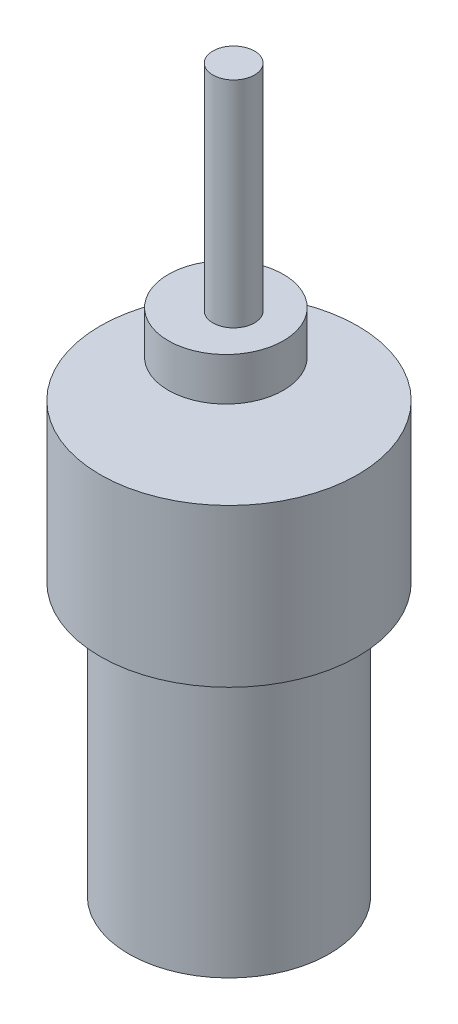
SolidWorks part; units mm, degrees
ref_plane "Front Plane" through (0, 0, 0) normal (0, 0, 1) x (1, 0, 0)
ref_plane "Top Plane" through (0, 0, 0) normal (0, 1, 0) x (1, 0, 0)
ref_plane "Right Plane" through (0, 0, 0) normal (1, 0, 0) x (0, 0, -1)
sketch "Sketch2" plane through (0, 0, 0) normal (0, 1, 0) x (1, 0, 0)
  circle A0 centre (0, 0) radius 14
  dimension "D1" = 28
extrude "Boss-Extrude1" add sketch "Sketch2" along normal blind 38
sketch "Sketch3" plane through (0, 38, 0) normal (0, 1, 0) x (1, 0, 0)
  circle A0 centre (0, 0) radius 18
  dimension "D1" = 36
extrude "Boss-Extrude2" add sketch "Sketch3" along normal blind 22
sketch "Sketch4" plane through (0, 60, 0) normal (0, 1, 0) x (1, 0, 0)
  circle A0 centre (-5.4402, 5.0029) radius 8.0381
extrude "Boss-Extrude3" add sketch "Sketch4" along normal blind 6
sketch "Sketch5" plane through (0, 66, 0) normal (0, 1, 0) x (1, 0, 0)
  circle A0 centre (-4.4842, 5.1388) radius 2.9076
extrude "Boss-Extrude4" add sketch "Sketch5" along normal blind 30
